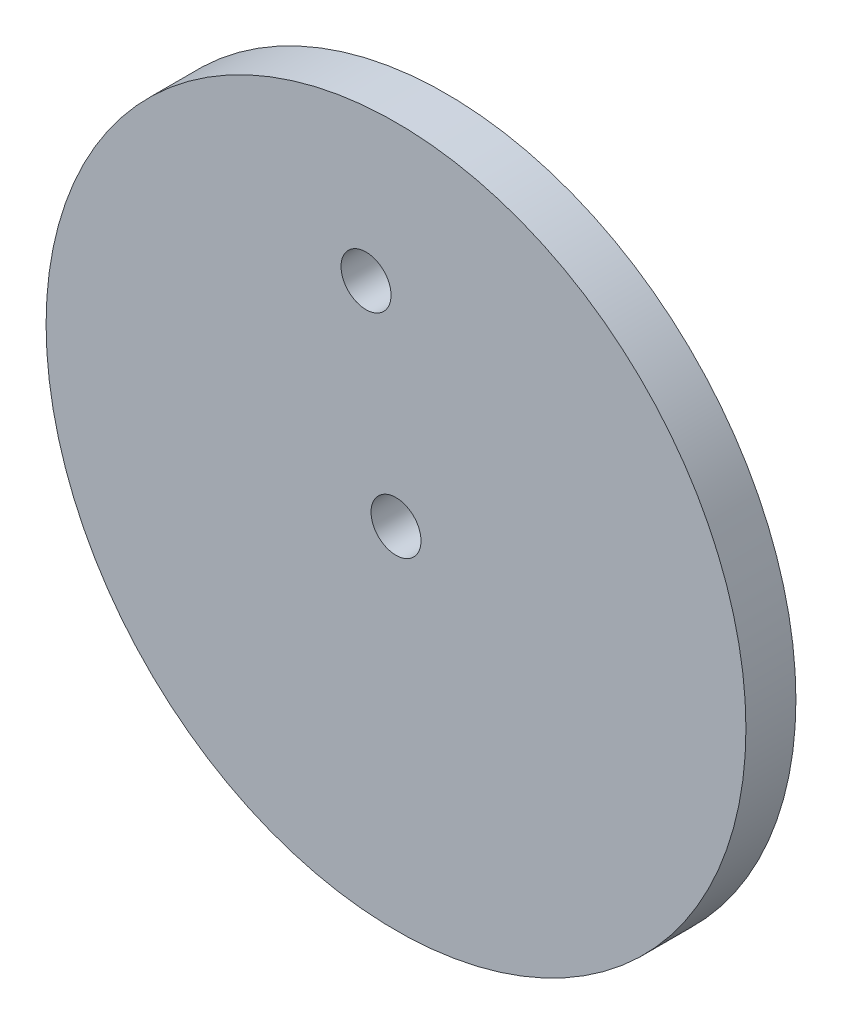
SolidWorks part; units mm, degrees
ref_plane "Front Plane" through (0, 0, 0) normal (0, 0, 1) x (1, 0, 0)
ref_plane "Top Plane" through (0, 0, 0) normal (0, 1, 0) x (1, 0, 0)
ref_plane "Right Plane" through (0, 0, 0) normal (1, 0, 0) x (0, 0, -1)
sketch "Sketch1" plane through (0, 0, 0) normal (0, 0, 1) x (1, 0, 0)
  circle A0 centre (0, 0) radius 22.225
  circle A1 centre (0, 0) radius 1.5875
  circle A2 centre (0, 0) radius 12.7 construction
  circle A3 centre (-1.9039, 12.5565) radius 1.5875
  dimension "D1" = 44.45
  dimension "D2" = 3.175
  dimension "D3" = 25.4
  dimension "D4" = 3.175
extrude "Boss-Extrude1" add sketch "Sketch1" along normal blind 3.175
